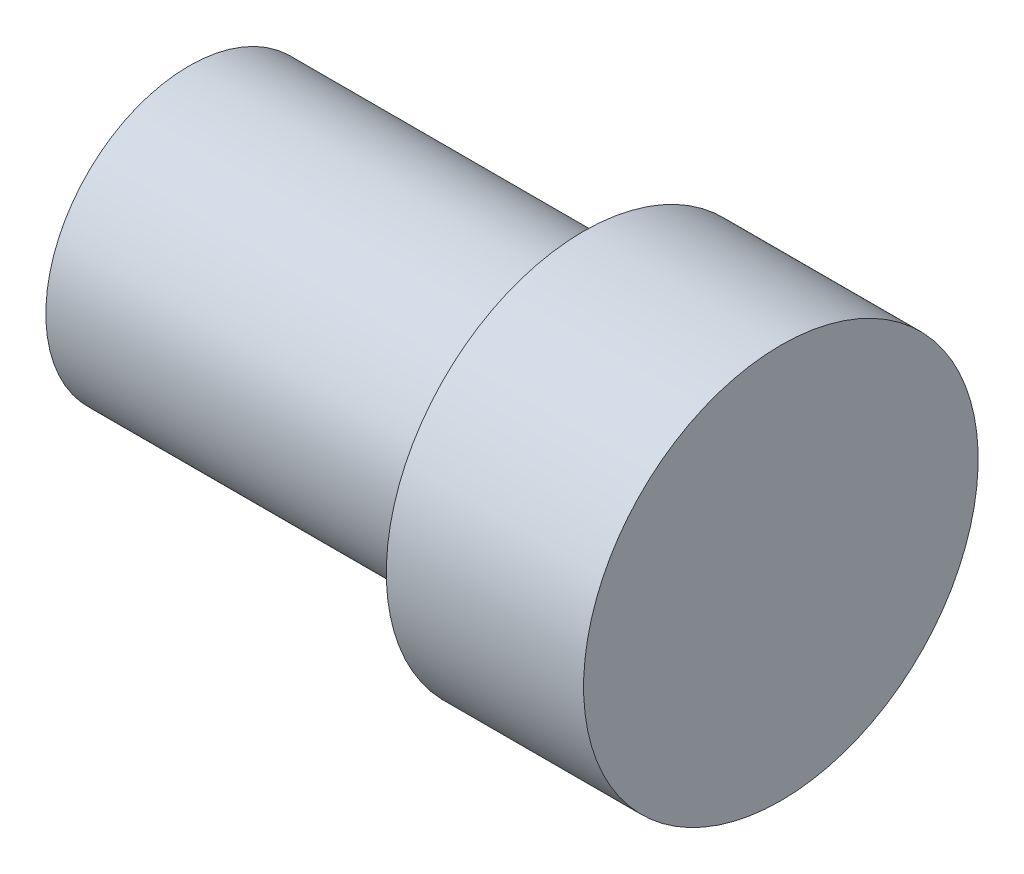
SolidWorks part; units mm, degrees
material "Maple"
ref_plane "Front Plane" through (0, 0, 0) normal (0, 0, 1) x (1, 0, 0)
ref_plane "Top Plane" through (0, 0, 0) normal (0, 1, 0) x (1, 0, 0)
ref_plane "Right Plane" through (0, 0, 0) normal (1, 0, 0) x (0, 0, -1)
sketch "Sketch1" plane through (0, 0, 0) normal (0, 0, 1) x (1, 0, 0)
  line L0 (0, 0) -> (20, 0)
  line L1 (20, 0) -> (20, 2.7431)
  line L2 (20, 2.7431) -> (30, 2.7431)
  line L3 (30, 2.7431) -> (30, -7.2569)
  line L4 (30, -7.2569) -> (0, -7.2569)
  line L5 (0, -7.2569) -> (0, 0)
  dimension "D1" = 10
  dimension "D3" = 30
  dimension "D4" = 20
revolve "Revolve1" add sketch "Sketch1" angle 360 about L4
